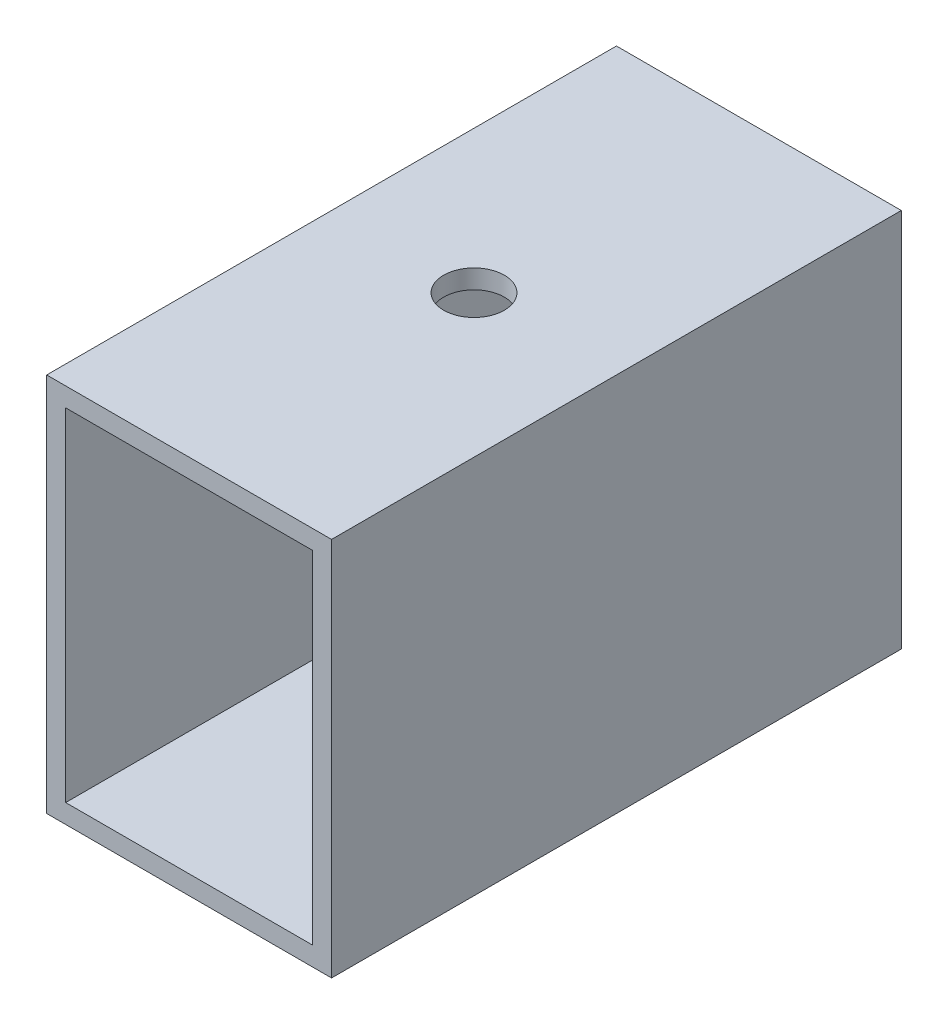
SolidWorks part; units mm, degrees
material "1060 合金"
ref_plane "前视基准面" through (0, 0, 0) normal (0, 0, 1) x (1, 0, 0)
ref_plane "上视基准面" through (0, 0, 0) normal (0, 1, 0) x (1, 0, 0)
ref_plane "右视基准面" through (0, 0, 0) normal (1, 0, 0) x (0, 0, -1)
other "Configuration Table"
sketch "草图1" plane through (0, 0, 0) normal (0, 0, 1) x (1, 0, 0)
  line L1 (0, 0) -> (15, 0)
  line L2 (0, 0) -> (0, -20)
  line L3 (0, -20) -> (15, -20)
  line L4 (15, 0) -> (15, -20)
  dimension "D1" = 20
  dimension "D2" = 15
extrude "拉伸-薄壁1" add sketch "草图1" along normal blind 30 thin
sketch "草图2" plane through (0, -20, 0) normal (0, -1, 0) x (1, 0, 0)
  circle A1 centre (7.5, 825) radius 2.6
  circle A2 centre (7.5, 825) radius 2.6
  dimension "D1" = 0
extrude "切除-拉伸1" [suppressed] cut sketch "草图2" against normal up to next
sketch "草图3" plane through (0, -20, 0) normal (0, -1, 0) x (1, 0, 0)
  line L0 (15, 30) -> (15, 0) construction
  line L1 (0, 30) -> (15, 30) construction
  circle A0 centre (7.5, 15) radius 1.6
  dimension "D3" = 3.2
  dimension "D1" = 7.5
  dimension "D2" = 15
extrude "切除-拉伸2" cut sketch "草图3" against normal through all
